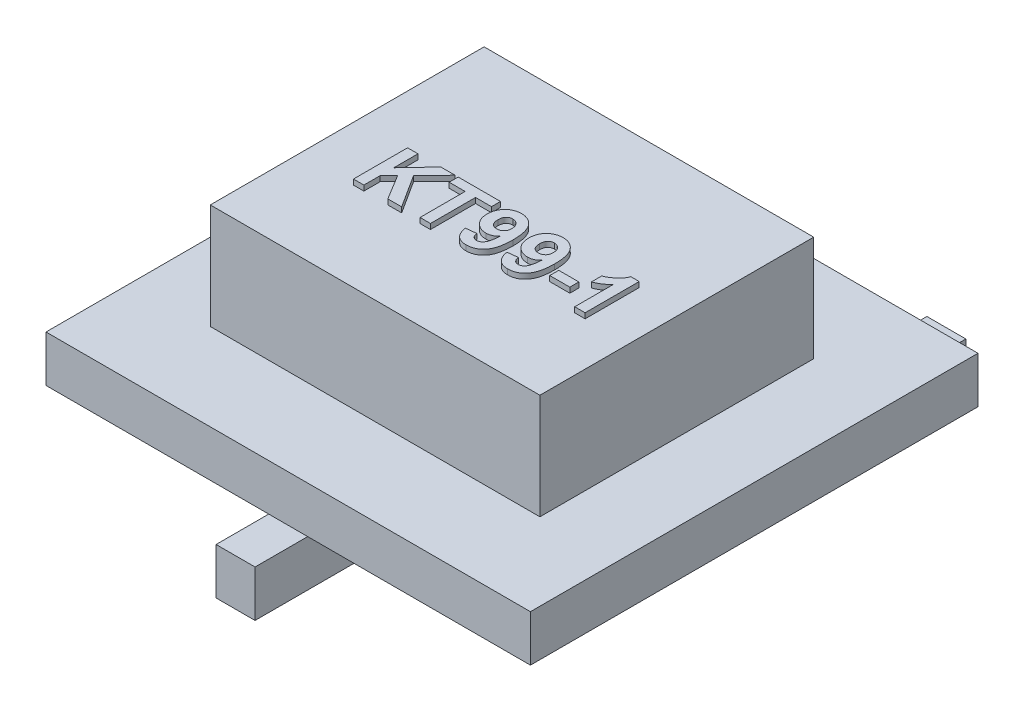
SolidWorks part; units mm, degrees
ref_plane "Спереди" through (0, 0, 0) normal (0, 0, 1) x (1, 0, 0)
ref_plane "Сверху" through (0, 0, 0) normal (0, 1, 0) x (1, 0, 0)
ref_plane "Справа" through (0, 0, 0) normal (1, 0, 0) x (0, 0, -1)
sketch "Эскиз1" plane through (0, 0, 0) normal (0, 1, 0) x (1, 0, 0)
  line L1 (-5.597, 4.9136) -> (-0.997, 4.9136)
  line L2 (-5.597, 4.9136) -> (-5.597, 0.6636)
  line L3 (-5.597, 0.6636) -> (-0.997, 0.6636)
  line L4 (-0.997, 4.9136) -> (-0.997, 0.6636)
  dimension "D1" = 4.6
  dimension "D2" = 4.25
extrude "Бобышка-Вытянуть1" add sketch "Эскиз1" along normal blind 0.44
sketch "Эскиз2" plane through (0, 0.44, 0) normal (0, 1, 0) x (1, 0, 0)
  line L0 (-5.597, 0.6636) -> (-0.997, 4.9136) construction
  line L1 (-5.597, 4.9136) -> (-0.997, 0.6636) construction
  line L3 (-4.862, 4.0886) -> (-1.732, 4.0886)
  line L4 (-4.862, 4.0886) -> (-4.862, 1.4886)
  line L5 (-4.862, 1.4886) -> (-1.732, 1.4886)
  line L6 (-1.732, 4.0886) -> (-1.732, 1.4886)
  line L7 (-4.862, 4.0886) -> (-1.732, 1.4886) construction
  line L8 (-4.862, 1.4886) -> (-1.732, 4.0886) construction
  point P4 (-3.297, 2.7886)
  point P19 (-1.4242, 4.3724)
  point P22 (-1.4242, 1.0652)
  point P25 (-5.0628, 1.0652)
  point P28 (-5.0628, 4.3724)
extrude "Бобышка-Вытянуть2" add sketch "Эскиз2" along normal blind 1
sketch "Эскиз3" plane through (0, 1.44, 0) normal (0, 1, 0) x (1, 0, 0)
  text T0 "<b>KT99-1</b>\r\n" font "Arial" height in points 2
extrude "Бобышка-Вытянуть3" add sketch "Эскиз3" along normal blind 0.05
sketch "Эскиз4" plane through (0, 0, 0) normal (0, -1, 0) x (1, 0, 0)
  line L0 (-5.597, -0.6636) -> (-4.5357, -1.6442) construction
  line L1 (-5.597, -4.9136) -> (-4.5357, -3.9331) construction
  line L2 (-1.982, -5.4136) -> (-1.982, -4.2886)
  line L3 (-3.482, -1.6442) -> (-3.482, -0.1636)
  line L4 (-1.982, -5.4136) -> (-1.612, -5.4136)
  line L5 (-3.482, -5.4136) -> (-3.482, -3.9331)
  line L6 (-3.112, -5.4136) -> (-3.112, -3.9331)
  line L7 (-3.482, -1.6442) -> (-4.7284, -1.6442)
  line L8 (-3.482, -5.4136) -> (-3.112, -5.4136)
  line L9 (-1.612, -4.2886) -> (-1.612, -5.4136)
  line L10 (-1.797, -4.2886) -> (-1.612, -4.2886)
  line L11 (-1.797, -4.2886) -> (-1.982, -4.2886)
  line L12 (-1.8655, -3.9331) -> (-3.112, -3.9331)
  line L13 (-4.982, -5.4136) -> (-4.982, -4.2886)
  line L14 (-1.8655, -3.9331) -> (-1.8655, -1.6442)
  line L15 (-4.612, -4.2886) -> (-4.612, -5.4136)
  line L16 (-4.797, -4.2886) -> (-4.612, -4.2886)
  line L17 (-4.797, -4.2886) -> (-4.982, -4.2886)
  line L18 (-1.8655, -1.6442) -> (-3.112, -1.6442)
  line L19 (-4.982, -5.4136) -> (-4.612, -5.4136)
  line L20 (-4.7284, -3.9331) -> (-4.7284, -1.6442)
  line L21 (-3.482, -0.1636) -> (-3.112, -0.1636)
  line L27 (-3.482, -3.9331) -> (-4.7284, -3.9331)
  line L28 (-3.112, -1.6442) -> (-3.112, -0.1636)
  line L31 (-2.0583, -1.6442) -> (-0.997, -0.6636) construction
  line L32 (-2.0583, -3.9331) -> (-0.997, -4.9136) construction
extrude "Бобышка-Вытянуть4" add sketch "Эскиз4" along normal blind 0.44
